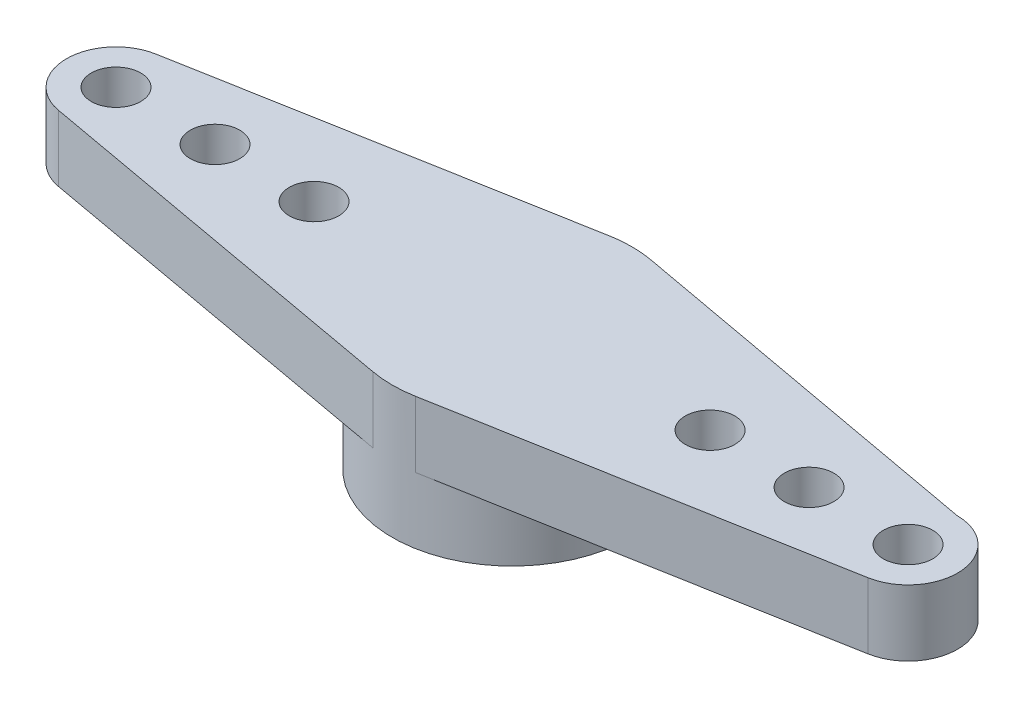
SolidWorks part; units mm, degrees
other "Markup1"
sketch "Sketch3" plane through (11.5, 2, 2.5) normal (0.4, 0.515, 0.7581) x (0.8844, 0, -0.4667)
ref_plane "Front Plane" through (0, 0, 0) normal (0, 0, 1) x (1, 0, 0)
ref_plane "Top Plane" through (0, 0, 0) normal (0, 1, 0) x (1, 0, 0)
ref_plane "Right Plane" through (0, 0, 0) normal (1, 0, 0) x (0, 0, -1)
sketch "Sketch1" plane through (0, 0, 0) normal (0, 1, 0) x (1, 0, 0)
  line L0 (-12.2662, 1.4762) -> (-0.6443, 3.5724)
  line L1 (-12.2663, -1.4762) -> (-0.6443, -3.5724)
  line L2 (0.6443, -3.5724) -> (12.2662, -1.4762)
  line L3 (0.6517, 3.571) -> (12, 1.5)
  arc A0 (-0.6443, -3.5724) -> (0.6443, -3.5724) centre (0, 0) ccw
  arc A1 (-12.2662, 1.4762) -> (-12.2663, -1.4762) centre (-12, 0) ccw
  arc A2 (12.2662, -1.4762) -> (12, 1.5) centre (12, 0) ccw
  arc A3 (0.6517, 3.571) -> (-0.6443, 3.5724) centre (0, 0) ccw
  dimension "D1" = 7.26
  dimension "D4" = 3
  dimension "D2" = 12
  dimension "D3" = 12
extrude "Boss-Extrude1" add sketch "Sketch1" along normal blind 2
sketch "Sketch2" plane through (0, 2, 0) normal (0, 1, 0) x (1, 0, 0)
  circle A0 centre (12, 0) radius 0.75
  arc A1 (12.2662, -1.4762) -> (12, 1.5) centre (12, 0) ccw construction
  circle A2 centre (9, 0) radius 0.75
  circle A3 centre (6, 0) radius 0.75
  point P6 (0, 0)
  point P10 (6.8179, 0)
  dimension "D1" = 1.5
  dimension "D3" = 3
  dimension "D2" = 3
extrude "Cut-Extrude1" cut sketch "Sketch2" against normal through all
mirror "Mirror1" about plane through (0, 0, 0) normal (1, 0, 0) of "Cut-Extrude1"
sketch "Sketch4" plane through (0, 0, 0) normal (0, -1, 0) x (1, 0, 0)
  circle A0 centre (0, 0) radius 3.63
  arc A1 (0.6443, 3.5724) -> (-0.6443, 3.5724) centre (0, 0) ccw construction
  circle A2 centre (0, 0) radius 2.88
  dimension "D1" = 5.76
extrude "Boss-Extrude2" add sketch "Sketch4" along normal blind 2
